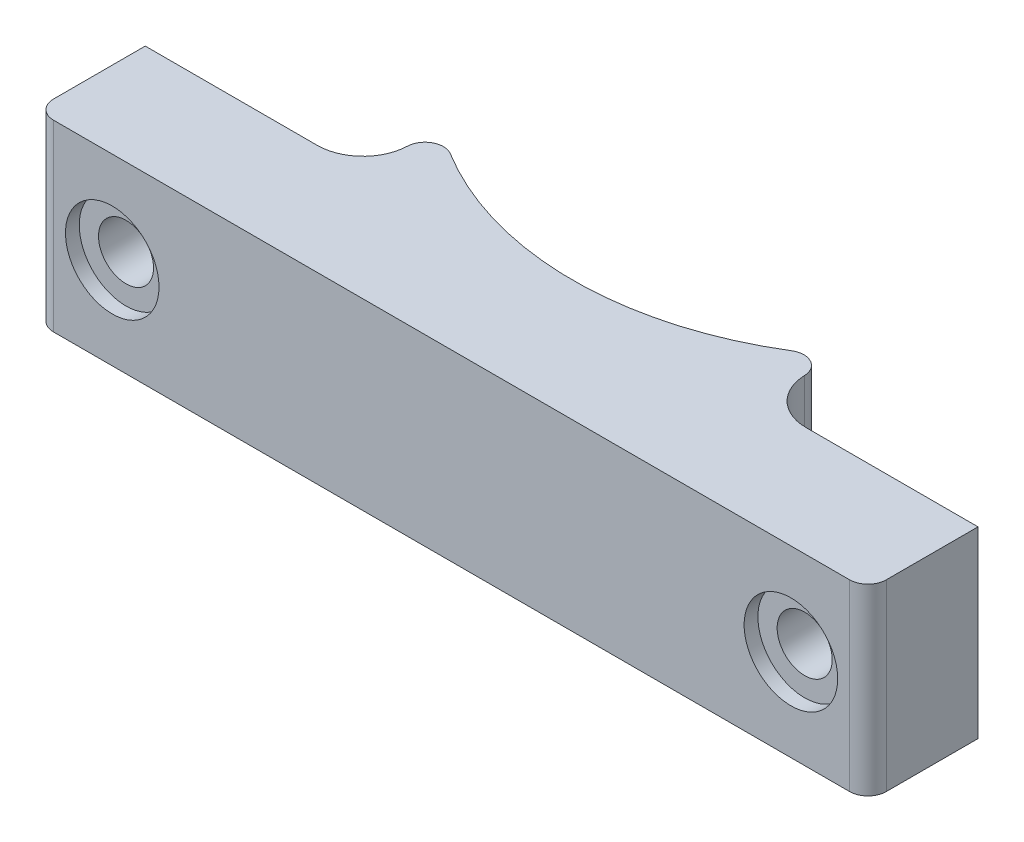
SolidWorks part; units mm, degrees
material "6061-T6 (SS)"
ref_plane "Front Plane" through (0, 0, 0) normal (0, 0, 1) x (1, 0, 0)
ref_plane "Top Plane" through (0, 0, 0) normal (0, 1, 0) x (1, 0, 0)
ref_plane "Right Plane" through (0, 0, 0) normal (1, 0, 0) x (0, 0, -1)
sketch "Sketch1" plane through (0, 0, 0) normal (0, 1, 0) x (1, 0, 0)
  line L0 (45.4, 0) -> (-45.4, 0)
  line L5 (-45.4, 0) -> (-45.4, 12)
  line L6 (-45.4, 12) -> (-26.65, 12)
  line L7 (-21.65, 17) -> (-21.65, 20.5659)
  line L8 (0, 0) -> (0, 70.0829) construction
  line L9 (21.65, 17) -> (21.65, 20.5659)
  line L10 (45.4, 12) -> (26.65, 12)
  line L11 (45.4, 0) -> (45.4, 12)
  arc A0 (-26.65, 12) -> (-21.65, 17) centre (-26.65, 17) ccw
  arc A1 (-21.65, 20.5659) -> (21.65, 20.5659) centre (0, 48.7) ccw
  arc A2 (26.65, 12) -> (21.65, 17) centre (26.65, 17) cw
  dimension "D3" = 5
  dimension "D4" = 71
  dimension "D1" = 12
  dimension "D2" = 18.75
  dimension "D5" = 45.4
  dimension "D6" = 48.7
extrude "Boss-Extrude1" add sketch "Sketch1" along normal blind 20
fillet "Fillet1" radius 2 2 edges at (21.65, 10, -20.5659) (-21.65, 10, -20.5659)
sketch "Sketch2" plane through (0, 0, 0) normal (0, 0, 1) x (1, 0, 0)
  line L0 (-45.4, 10) -> (45.4, 10)
  line L1 (-45.4, 20) -> (-45.4, 0) construction
  line L2 (45.4, 20) -> (45.4, 0) construction
  line L3 (-37, 20) -> (-37, 10)
  line L4 (-45.4, 20) -> (45.4, 20) construction
  line L6 (37, 20) -> (37, 10)
  dimension "D1" = 8.4
  dimension "D2" = 8.4
hole_wizard "Hole1" positions "Sketch3" profile "Sketch4" legacy
sketch "Sketch3" plane through (0, 0, 0) normal (0, 0, 1) x (1, 0, 0)
  point P0 (-37, 10)
  point P3 (37, 10)
sketch "Sketch4" plane through (-37, 10, 0) normal (1, 0, 0) x (0, -1, 0)
  line L0 (0, 0) -> (0, 22.0626)
  line L1 (0, 22.0626) -> (3, 20.26)
  line L2 (3, 20.26) -> (3, 1.5)
  line L3 (3, 1.5) -> (5.1, 1.5)
  line L4 (5.1, 0) -> (0, 0)
  line L5 (0, -11.3109) -> (0, 121.1557) construction
  line L6 (0, 22.0626) -> (-3, 20.26) construction
  line L7 (5.1, 1.5) -> (5.1, 0)
  dimension "Depth" = 20.26
  dimension "Drill Angle" = 118
  dimension "Diameter" = 6
  dimension "C-Bore Diameter" = 10.2
  dimension "C-Bore Depth" = 1.5
fillet "Fillet2" radius 2 2 edges at (45.4, 10, 0) (-45.4, 10, 0)
